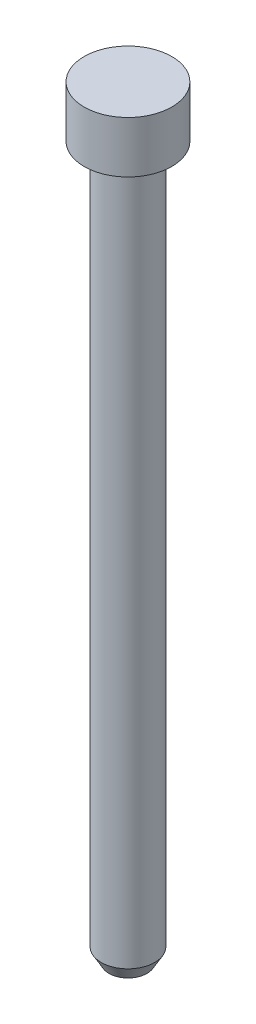
SolidWorks part; units mm, degrees
ref_plane "Front" through (0, 0, 0) normal (0, 0, 1) x (1, 0, 0)
ref_plane "Top" through (0, 0, 0) normal (0, 1, 0) x (1, 0, 0)
ref_plane "Right" through (0, 0, 0) normal (1, 0, 0) x (0, 0, -1)
sketch "Sketch1" plane through (0, 0, 0) normal (0, 1, 0) x (1, 0, 0)
  circle A0 centre (0, 0) radius 2.6
  dimension "D1" = 5.2
extrude "Boss-Extrude1" add sketch "Sketch1" along normal blind 69
sketch "Sketch2" plane through (0, 69, 0) normal (0, 1, 0) x (1, 0, 0)
  circle A0 centre (0, 0) radius 4.25
  dimension "D1" = 8.5
extrude "Boss-Extrude2" add sketch "Sketch2" along normal blind 5
fillet "Fillet1" radius 0.5 1 edges at (0, 69, 2.6)
chamfer "Chamfer1" distance 0.75 angle 60 1 edges at (0, 0, 2.6)
